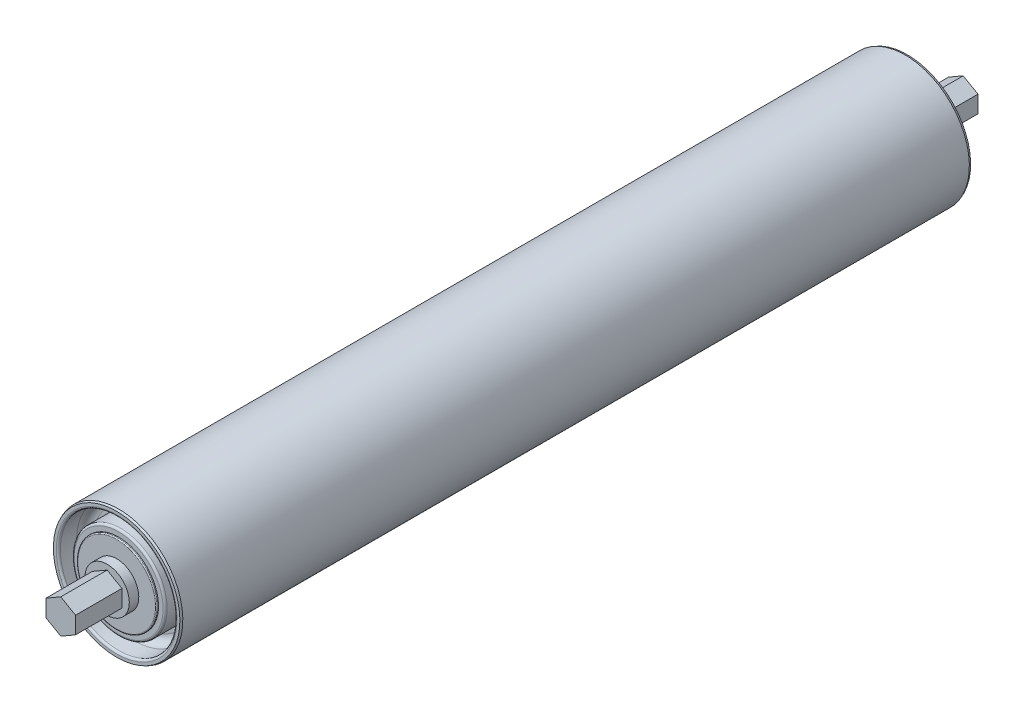
SolidWorks part; units mm, degrees
ref_plane "Front Plane" through (0, 0, 0) normal (0, 0, 1) x (1, 0, 0)
ref_plane "Top Plane" through (0, 0, 0) normal (0, 1, 0) x (1, 0, 0)
ref_plane "Right Plane" through (0, 0, 0) normal (1, 0, 0) x (0, 0, -1)
sketch "Sketch1" plane through (0, 0, 0) normal (1, 0, 0) x (0, 0, -1)
  line L0 (-169.8625, 0) -> (169.8625, 0) construction
  line L1 (-148.0344, 24.13) -> (148.0344, 24.13)
  line L2 (0, 24.13) -> (0, 0) construction
  line L3 (-169.8625, 0) -> (-169.8625, 5.5562)
  line L4 (-169.8625, 5.5562) -> (-148.0344, 5.5562)
  line L5 (-153.9875, 5.5562) -> (-153.9875, -5.5562) construction
  line L6 (153.9875, 5.5562) -> (153.9875, -5.5562) construction
  line L7 (-153.9875, -5.5562) -> (153.9875, -5.5562) construction
  line L8 (-148.0344, 24.13) -> (-148.0344, 0) construction
  line L9 (-152.4, 8.3344) -> (-152.4, 0)
  line L10 (-152.4, 8.3344) -> (-148.0344, 8.3344)
  line L11 (152.4, 8.3344) -> (148.0344, 8.3344)
  line L12 (152.4, 8.3344) -> (152.4, 0)
  line L13 (169.8625, 5.5563) -> (148.0344, 5.5563)
  line L14 (169.8625, 0) -> (169.8625, 5.5563)
  line L15 (-148.8281, 15.0019) -> (-148.0661, 15.0019) construction
  line L16 (-148.0344, 24.13) -> (-148.8281, 23.8125)
  line L17 (-148.8281, 23.8125) -> (-148.8281, 8.3344)
  line L18 (148.0344, 24.13) -> (148.8281, 23.8125)
  line L19 (148.8281, 23.8125) -> (148.8281, 8.3344)
  line L20 (-148.0661, 15.0019) -> (-148.0661, 17.5022) construction
  line L22 (-148.0661, 17.5022) -> (-138.9062, 17.5022) construction
  line L23 (-138.9062, 17.5022) -> (-138.9062, 21.971) construction
  line L24 (-138.9062, 21.971) -> (-148.8281, 21.971) construction
  arc A1 (-141.9543, 21.971) -> (-138.9063, 18.923) centre (-141.9543, 18.923) cw construction
  arc A2 (-148.8281, 22.733) -> (-148.0661, 21.971) centre (-148.0661, 22.733) ccw construction
  arc A3 (-148.0661, 16.7402) -> (-147.3041, 17.5022) centre (-147.3041, 16.7402) cw construction
  arc A4 (-148.8281, 14.6209) -> (-148.4471, 15.0019) centre (-148.4471, 14.6209) cw construction
  point P11 (-153.9875, 0)
  point P12 (153.9875, 0)
  point P13 (0, -5.5562)
  point P24 (-124.1425, 0)
  point P27 (124.1425, 0)
  point P32 (-138.9062, 19.7366)
  dimension "D14" = 3.048
  dimension "D15" = 0.762
  dimension "D16" = 0.381
  dimension "Overall Width" = 339.725
  dimension "Rollar Diameter" = 48.26
  dimension "Hex Axle Size" = 11.1125
  dimension "BF" = 307.975
  dimension "D2" = 16.6687
  dimension "D1" = 1.5875
  dimension "D5" = 15.875
  dimension "D6" = 45.72
  dimension "D7" = 45.72
  dimension "D3" = 4.3656
  dimension "D8" = 47.625
  dimension "D10" = 0.762
  dimension "D9" = 35.0044
  dimension "D11" = 30.0038
  dimension "D12" = 43.942
  dimension "D13" = 13.4937
  dimension "Rollar Width" = 297.6562
sketch "Sketch5" plane through (0, 0, 0) normal (0, 0, 1) x (1, 0, 0)
  circle A0 centre (0, 0) radius 24.13
  dimension "D1" = 48.26
sketch "Sketch3" plane through (0, 0, 0) normal (1, 0, 0) x (0, 0, -1)
  line L0 (169.8625, 5.5563) -> (148.0344, 5.5563) construction
  line L1 (169.8625, 0) -> (169.8625, 5.5563) construction
  line L2 (-169.8625, 0) -> (-169.8625, 5.5562) construction
  line L3 (-169.8625, 5.5562) -> (-148.0344, 5.5562) construction
  line L4 (148.8281, 23.8125) -> (148.8281, 8.3344) construction
  line L5 (148.0344, 24.13) -> (148.8281, 23.8125) construction
  line L6 (-148.0344, 24.13) -> (148.0344, 24.13) construction
  line L7 (-148.0344, 24.13) -> (-148.8281, 23.8125) construction
  line L8 (-148.8281, 23.8125) -> (-148.8281, 8.3344) construction
  line L9 (152.4, 8.3344) -> (148.0344, 8.3344) construction
  line L10 (152.4, 8.3344) -> (152.4, 0) construction
  line L11 (-152.4, 8.3344) -> (-152.4, 0) construction
  line L12 (-152.4, 8.3344) -> (-148.0344, 8.3344) construction
  line L13 (169.8625, 5.5563) -> (152.4, 5.5563)
  line L14 (169.8625, 0) -> (169.8625, 5.5563)
  line L15 (-169.8625, 0) -> (-169.8625, 5.5562)
  line L16 (-169.8625, 5.5562) -> (-152.4, 5.5562)
  line L17 (148.8281, 23.8125) -> (148.8281, 8.3344)
  line L18 (148.0344, 24.13) -> (148.8281, 23.8125)
  line L19 (-148.0344, 24.13) -> (148.0344, 24.13)
  line L20 (-148.0344, 24.13) -> (-148.8281, 23.8125)
  line L21 (-148.8281, 23.8125) -> (-148.8281, 8.3344)
  line L22 (152.4, 8.3344) -> (148.8281, 8.3344)
  line L23 (152.4, 8.3344) -> (152.4, 5.5563)
  line L24 (-152.4, 8.3344) -> (-152.4, 5.5562)
  line L25 (-152.4, 8.3344) -> (-148.8281, 8.3344)
  line L26 (-169.8625, 0) -> (169.8625, 0)
revolve "Revolve1" add sketch "Sketch3" angle 360 about L0
sketch "Sketch4" plane through (0, 0, 169.8625) normal (0, 0, 1) x (1, 0, 0)
  line L1 (0, 6.4158) -> (-5.5562, 3.2079)
  line L2 (-5.5562, 3.2079) -> (-5.5562, -3.2079)
  line L3 (-5.5562, -3.2079) -> (0, -6.4158)
  line L4 (0, -6.4158) -> (5.5562, -3.2079)
  line L5 (5.5562, -3.2079) -> (5.5562, 3.2079)
  line L6 (5.5562, 3.2079) -> (0, 6.4158)
  circle A0 centre (0, 0) radius 5.5562 construction
extrude "Boss-Extrude1" add sketch "Sketch4" against normal up to surface (339.725 mm away) up to face at (0, -5.5562, -169.8625)
sketch "Sketch6" plane through (0, 0, 0) normal (1, 0, 0) x (0, 0, -1)
  line L0 (-138.9062, 21.971) -> (-148.8281, 21.971) construction
  line L1 (-138.9062, 17.5022) -> (-138.9062, 21.971) construction
  line L2 (-148.0661, 17.5022) -> (-138.9062, 17.5022) construction
  line L3 (-148.0661, 15.0019) -> (-148.0661, 17.5022) construction
  line L4 (-148.8281, 15.0019) -> (-148.0661, 15.0019) construction
  line L5 (-141.9543, 21.971) -> (-148.0661, 21.971)
  line L6 (-138.9062, 17.5022) -> (-138.9062, 18.923)
  line L7 (-147.3041, 17.5022) -> (-138.9062, 17.5022)
  line L8 (-148.0661, 15.0019) -> (-148.0661, 16.7402)
  line L9 (-148.4471, 15.0019) -> (-148.0661, 15.0019)
  line L10 (-148.8281, 22.733) -> (-148.8281, 14.6209)
  arc A0 (-148.8281, 22.733) -> (-148.0661, 21.971) centre (-148.0661, 22.733) ccw construction
  arc A1 (-138.9062, 18.923) -> (-141.9543, 21.971) centre (-141.9543, 18.923) ccw construction
  arc A2 (-147.3041, 17.5022) -> (-148.0661, 16.7402) centre (-147.3041, 16.7402) ccw construction
  arc A3 (-148.4471, 15.0019) -> (-148.8281, 14.6209) centre (-148.4471, 14.6209) ccw construction
  arc A4 (-148.8281, 22.733) -> (-148.0661, 21.971) centre (-148.0661, 22.733) ccw
  arc A5 (-138.9062, 18.923) -> (-141.9543, 21.971) centre (-141.9543, 18.923) ccw
  arc A6 (-147.3041, 17.5022) -> (-148.0661, 16.7402) centre (-147.3041, 16.7402) ccw
  arc A7 (-148.4471, 15.0019) -> (-148.8281, 14.6209) centre (-148.4471, 14.6209) ccw
revolve "Cut-Revolve1" cut sketch "Sketch6" angle 360 about L0
mirror "Mirror2" about plane through (0, 0, 0) normal (0, 0, 1) of "Cut-Revolve1"
ref_plane "Contact Plane 1" through (0, 24.13, 0) normal (0, 1, 0) x (1, 0, 0)
equation "\"D2@Sketch1\"=\"Hex Axle Size@Sketch1\"*1.5"
equation "\"D7@Sketch1\"=\"D6@Sketch1\""
equation "\"D9@Sketch1\"=\"D2@Sketch1\"*2.1"
equation "\"D11@Sketch1\"=\"D2@Sketch1\"*1.8"
equation "\"D12@Sketch1\"=1.7+\"D10@Sketch1\""
equation "\"D16@Sketch1\"=\"D15@Sketch1\"/2"
